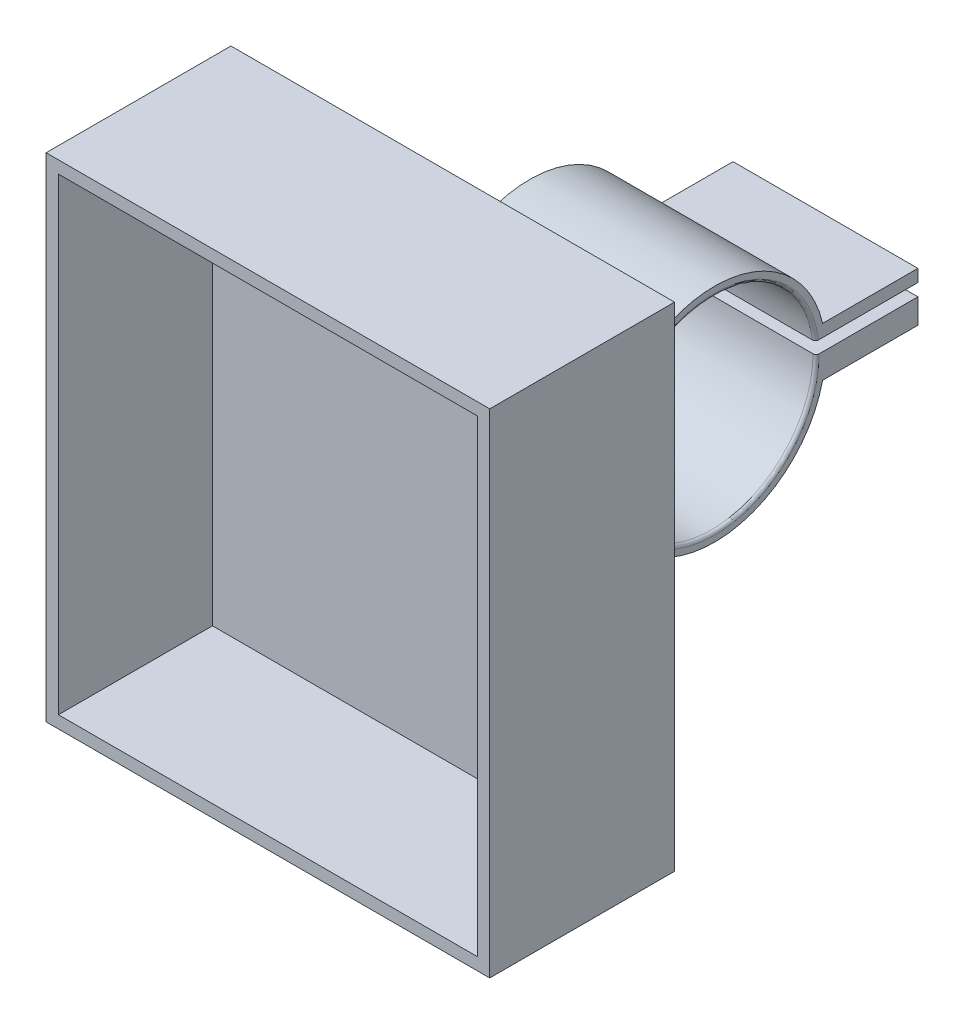
SolidWorks part; units mm, degrees
ref_plane "Plano frontal" through (0, 0, 0) normal (0, 0, 1) x (1, 0, 0)
ref_plane "Plano superior" through (0, 0, 0) normal (0, 1, 0) x (1, 0, 0)
ref_plane "Plano direito" through (0, 0, 0) normal (1, 0, 0) x (0, 0, -1)
sketch "Esboço1" plane through (0, 0, 0) normal (0, 0, 1) x (1, 0, 0)
  line L1 (36, -40) -> (-36, -40)
  line L2 (36, -40) -> (36, 40)
  line L3 (36, 40) -> (-36, 40)
  line L4 (-36, -40) -> (-36, 40)
  line L5 (36, -40) -> (-36, 40) construction
  line L6 (36, 40) -> (-36, -40) construction
  point P0 (0, 0)
  dimension "D1" = 72
  dimension "D2" = 80
extrude "Ressalto-extrusão1" add sketch "Esboço1" along normal blind 30
sketch "Esboço3" plane through (0, 0, 30) normal (0, 0, 1) x (1, 0, 0)
  line L1 (34, -38) -> (-34, -38)
  line L2 (34, -38) -> (34, 38)
  line L3 (34, 38) -> (-34, 38)
  line L4 (-34, -38) -> (-34, 38)
  line L5 (34, -38) -> (-34, 38) construction
  line L6 (34, 38) -> (-34, -38) construction
  point P0 (0, 0)
  dimension "D1" = 68
  dimension "D2" = 76
extrude "Corte-extrusão1" cut sketch "Esboço3" against normal blind 25
sketch "Esboço7" plane through (0, 0, 0) normal (0, 0, -1) x (-1, 0, 0)
  circle A0 centre (0, 0) radius 10.25
  dimension "D1" = 20.5
extrude "Ressalto-extrusão3" add sketch "Esboço7" along normal blind 15
fillet "Filete1" radius 4 1 edges at (-10.25, 0, 0)
sketch "Esboço9" plane through (0, 0, 0) normal (1, 0, 0) x (0, 0, -1)
  circle A0 centre (27.4794, 0) radius 18
  dimension "D1" = 36
extrude "Ressalto-extrusão4" add sketch "Esboço9" along normal blind 15 and the other way blind 15
sketch "Esboço10" plane through (15, 0, 0) normal (1, 0, 0) x (0, 0, -1)
  circle A0 centre (27.4794, 0) radius 16.5
  point P0 (27.4794, 0)
  dimension "D1" = 33
extrude "Corte-extrusão2" cut sketch "Esboço10" against normal blind 40
sketch "Esboço11" plane through (0, 0, 0) normal (1, 0, 0) x (0, 0, -1)
  line L1 (60.4926, 0) -> (60.4926, 4)
  line L2 (60.4926, 4) -> (45.0293, 4)
  line L3 (60.4926, 0) -> (60.4926, -4)
  line L4 (60.4926, -4) -> (45.0293, -4)
  line L5 (45.0293, 4) -> (45.0293, -4)
  circle A0 centre (27.4794, 0) radius 18 construction
  dimension "D1" = 15.4633
  dimension "D2" = 4
  dimension "D3" = 4
  dimension "D4" = 8
extrude "Ressalto-extrusão5" add sketch "Esboço11" along normal blind 15 and the other way blind 15
sketch "Esboço12" plane through (15, 0, 0) normal (1, 0, 0) x (0, 0, -1)
  line L1 (60.4926, -4) -> (60.4926, 4) construction
  line L2 (60.4926, 0) -> (60.4926, 2)
  line L4 (60.4926, 2) -> (43.4926, 2)
  line L5 (43.4926, 2) -> (43.4926, 0)
  line L7 (43.4926, 0) -> (60.4926, 0)
  dimension "D1" = 17
  dimension "D2" = 2
  dimension "D3" = 2
extrude "Corte-extrusão3" cut sketch "Esboço12" against normal blind 40
fillet "Filete2" radius 0.5 1 edges at (15, -1.0018, -11.0098)
fillet "Filete3" radius 0.5 1 edges at (-15, -1.0018, -11.0098)
